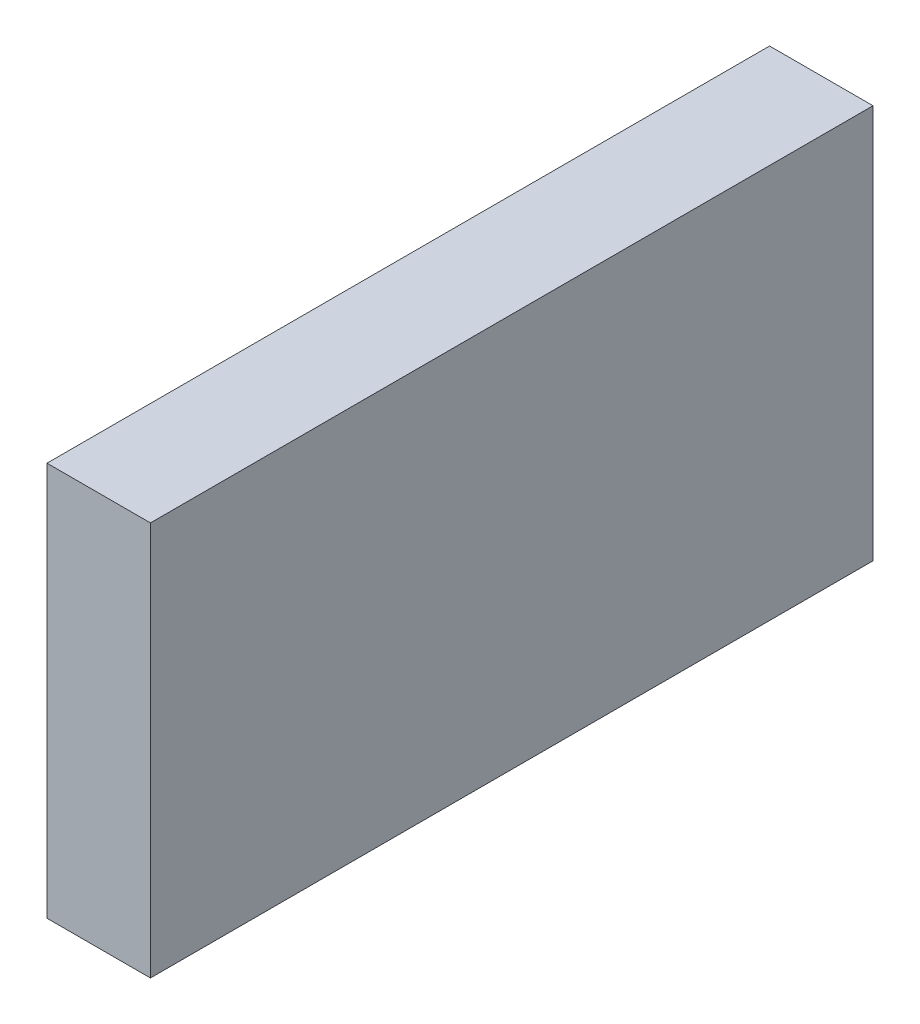
SolidWorks part; units mm, degrees
ref_plane "Front Plane" through (0, 0, 0) normal (0, 0, 1) x (1, 0, 0)
ref_plane "Top Plane" through (0, 0, 0) normal (0, 1, 0) x (1, 0, 0)
ref_plane "Right Plane" through (0, 0, 0) normal (1, 0, 0) x (0, 0, -1)
sketch "Sketch1" plane through (0, 0, 0) normal (0, 0, 1) x (1, 0, 0)
  line L1 (-2.4259, -22.2633) -> (7.5741, -22.2633)
  line L2 (-2.4259, -22.2633) -> (-2.4259, 15.8367)
  line L3 (-2.4259, 15.8367) -> (7.5741, 15.8367)
  line L4 (7.5741, -22.2633) -> (7.5741, 15.8367)
  line L5 (-2.4259, -22.2633) -> (7.5741, 15.8367) construction
  line L6 (-2.4259, 15.8367) -> (7.5741, -22.2633) construction
  point P0 (2.5741, -3.2133)
  dimension "D1" = 38.1
  dimension "D2" = 10
extrude "Boss-Extrude1" add sketch "Sketch1" along normal blind 69.85
